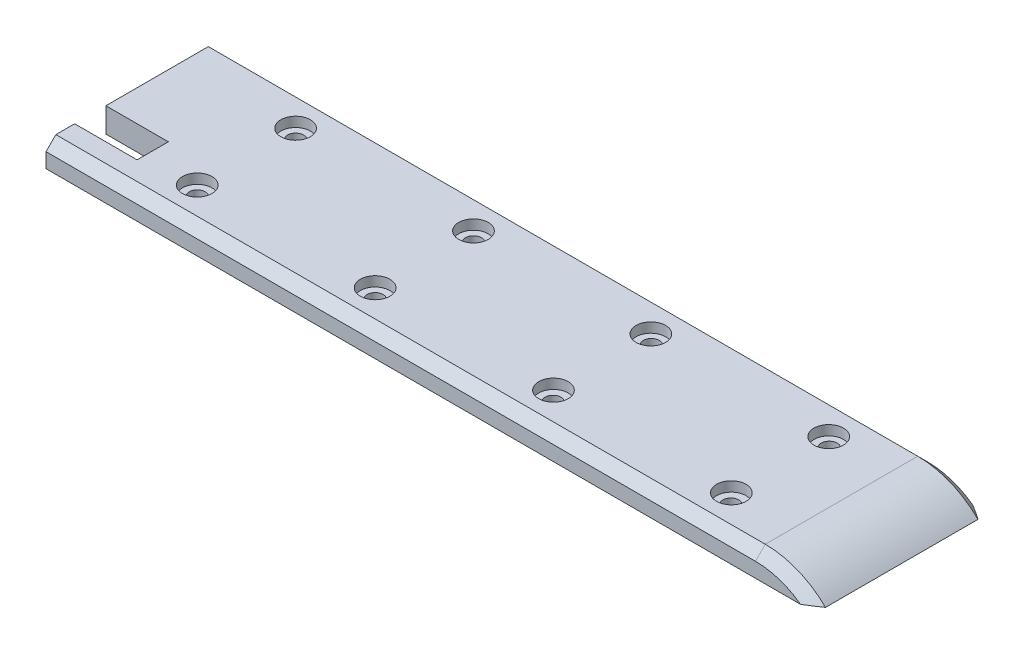
SolidWorks part; units mm, degrees
ref_plane "Front Plane" through (0, 0, 0) normal (0, 0, 1) x (1, 0, 0)
ref_plane "Top Plane" through (0, 0, 0) normal (0, 1, 0) x (1, 0, 0)
ref_plane "Right Plane" through (0, 0, 0) normal (1, 0, 0) x (0, 0, -1)
sketch "Sketch1" plane through (0, 0, 0) normal (0, 0, 1) x (1, 0, 0)
  line L0 (-75, 0) -> (75, 0) construction
  line L4 (-75, 17.5) -> (75, 17.5)
  line L6 (87.2474, 12.5) -> (-87.2474, 12.5)
  arc A2 (-75, 17.5) -> (-87.2474, 12.5) centre (-75, 0) ccw
  arc A3 (87.2474, 12.5) -> (75, 17.5) centre (75, 0) ccw
  point P2 (0, 0)
  point P5 (0, 0)
  dimension "D1" = 17.5
  dimension "D2" = 150
  dimension "D3" = 5
extrude "Boss-Extrude1" add sketch "Sketch1" along normal mid plane 35
sketch "Sketch2" plane through (0, 0, 0) normal (0, 0, 1) x (1, 0, 0)
  line L0 (75, 17.5) -> (-75, 17.5) construction
  line L1 (-87.2474, 12.5) -> (-69.2474, 12.5)
  line L2 (-87.2474, 12.5) -> (-87.2474, 17.5)
  line L3 (-87.2474, 17.5) -> (-69.2474, 17.5)
  line L4 (-69.2474, 12.5) -> (-69.2474, 17.5)
  dimension "D1" = 18
extrude "Cut-Extrude1" cut sketch "Sketch2" against normal mid plane 35
sketch "Sketch3" plane through (0, 12.5, 0) normal (0, -1, 0) x (1, 0, 0)
  line L0 (-69.2474, -17.5) -> (-69.2474, 17.5) construction
  line L1 (-69.2474, -17.5) -> (87.2474, -17.5) construction
  circle A0 centre (-46, -10) radius 1.625
  circle A1 centre (-9.8333, -10) radius 1.625
  circle A2 centre (26.3333, -10) radius 1.625
  circle A3 centre (62.5, -10) radius 1.625
  dimension "D1" = 3.25
  dimension "D2" = 36.1667
  dimension "D3" = 36.1667
  dimension "D4" = 36.1667
  dimension "D5" = 23.2474
  dimension "D6" = 7.5
extrude "Cut-Extrude2" cut sketch "Sketch3" against normal up to surface (5 mm away) up to face at (2.8763, 17.5, 0)
sketch "Sketch4" plane through (0, 17.5, 0) normal (0, 1, 0) x (1, 0, 0)
  circle A0 centre (62.5, 9.9) radius 3
  circle A1 centre (26.3333, 9.9) radius 3
  circle A2 centre (-9.8333, 10) radius 3
  circle A3 centre (-46, 10) radius 3
  dimension "D1" = 6
extrude "Cut-Extrude3" cut sketch "Sketch4" against normal blind 2
mirror "Mirror1" about plane through (0, 0, 0) normal (0, 0, 1) of "Cut-Extrude3", "Cut-Extrude2"
chamfer "Chamfer1" distance 2 angle 45 4 edges at (81.6144, 16.2019, 17.5) (2.8763, 17.5, 17.5) (81.6144, 16.2019, -17.5) (2.8763, 17.5, -17.5)
sketch "Sketch5" plane through (0, 17.5, 0) normal (0, 1, 0) x (1, 0, 0)
  line L0 (-87.75, -5.325) -> (-62.25, -5.325) construction
  line L1 (-69.2474, -5.325) -> (-56.5474, -5.325)
  line L2 (-69.2474, -5.325) -> (-69.2474, -11.675)
  line L3 (-69.2474, -11.675) -> (-56.5474, -11.675)
  line L4 (-56.5474, -5.325) -> (-56.5474, -11.675)
  line L5 (-69.285, -5.325) -> (-71.0187, -5.325) construction
  line L6 (-69.2474, 15.5) -> (-69.2474, -15.5) construction
  dimension "D1" = 6.35
  dimension "D2" = 12.7
extrude "Cut-Extrude4" cut sketch "Sketch5" against normal up to surface (5 mm away) up to face at (-44.375, 12.5, 10)
